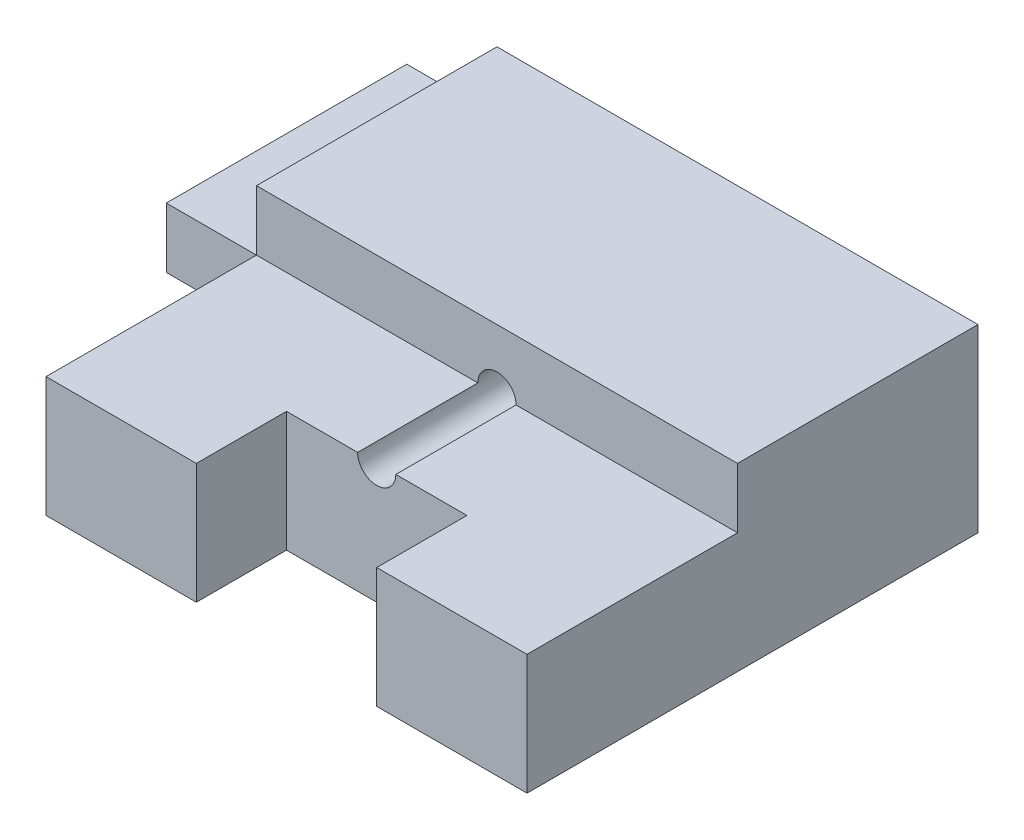
SolidWorks part; units mm, degrees
ref_plane "Front Plane" through (0, 0, 0) normal (0, 0, 1) x (1, 0, 0)
ref_plane "Top Plane" through (0, 0, 0) normal (0, 1, 0) x (1, 0, 0)
ref_plane "Right Plane" through (0, 0, 0) normal (1, 0, 0) x (0, 0, -1)
sketch "Sketch2" plane through (0, 0, 0) normal (0, 1, 0) x (1, 0, 0)
  line L1 (0, 0) -> (-16, 0)
  line L2 (0, 0) -> (0, 15)
  line L3 (0, 15) -> (-16, 15)
  line L4 (-16, 0) -> (-16, 15)
  dimension "D1" = 15
  dimension "D2" = 16
extrude "Boss-Extrude2" add sketch "Sketch2" along normal blind 6
sketch "Sketch6" plane through (0, 6, 0) normal (0, 1, 0) x (1, 0, 0)
  line L1 (-16, 0) -> (0, 0)
  line L2 (-16, 0) -> (-16, 7)
  line L3 (-16, 7) -> (0, 7)
  line L4 (0, 0) -> (0, 7)
  dimension "D1" = 16
  dimension "D2" = 7
extrude "Cut-Extrude3" cut sketch "Sketch6" against normal blind 2
sketch "Sketch7" plane through (0, 4, 0) normal (0, 1, 0) x (1, 0, 0)
  line L1 (-16, 0) -> (0, 0) construction
  line L3 (-11, 0) -> (-5, 0)
  line L4 (-11, 0) -> (-11, 3)
  line L5 (-11, 3) -> (-5, 3)
  line L6 (-5, 0) -> (-5, 3)
  dimension "D2" = 6
  dimension "D3" = 3
extrude "Cut-Extrude4" cut sketch "Sketch7" against normal through all
sketch "Sketch12" plane through (0, 0, -15) normal (0, 0, -1) x (-1, 0, 0)
  line L2 (8, 0) -> (8, 4) construction
  line L3 (0, 0) -> (16, 0) construction
  circle A0 centre (8, 4) radius 0.635
  dimension "D1" = 1.27
extrude "Cut-Extrude5" cut sketch "Sketch12" against normal blind 100
sketch "Sketch13" plane through (-16, 0, 0) normal (-1, 0, 0) x (0, 0, 1)
  line L0 (-7, 4) -> (-7, 0) construction
  line L1 (-15, 0) -> (0, 0) construction
  line L2 (-15, 6) -> (-15, 0) construction
  line L3 (-15, 4) -> (-7, 4)
  line L4 (-15, 4) -> (-15, 2)
  line L5 (-15, 2) -> (-7, 2)
  line L6 (-7, 4) -> (-7, 2)
extrude "Boss-Extrude3" add sketch "Sketch13" along normal blind 3
